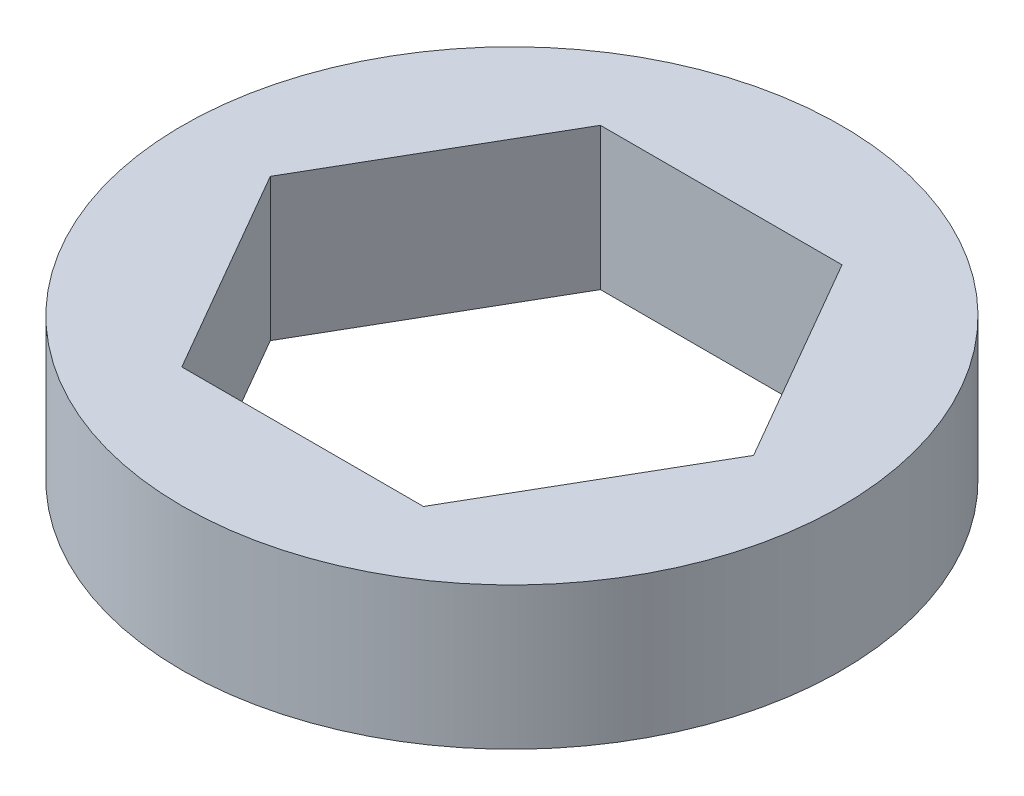
SolidWorks part; units mm, degrees
ref_plane "Front Plane" through (0, 0, 0) normal (0, 0, 1) x (1, 0, 0)
ref_plane "Top Plane" through (0, 0, 0) normal (0, 1, 0) x (1, 0, 0)
ref_plane "Right Plane" through (0, 0, 0) normal (1, 0, 0) x (0, 0, -1)
sketch "Sketch1" plane through (0, 0, 0) normal (0, 1, 0) x (1, 0, 0)
  line L1 (-7.3323, 0) -> (-3.6662, -6.35)
  line L2 (-3.6662, -6.35) -> (3.6662, -6.35)
  line L3 (3.6662, -6.35) -> (7.3323, 0)
  line L4 (7.3323, 0) -> (3.6662, 6.35)
  line L5 (3.6662, 6.35) -> (-3.6662, 6.35)
  line L6 (-3.6662, 6.35) -> (-7.3323, 0)
  circle A0 centre (0, 0) radius 10
  circle A1 centre (0, 0) radius 6.35 construction
  dimension "D2" = 20
  dimension "D1" = 12.7
extrude "Boss-Extrude1" add sketch "Sketch1" along normal blind 4.318
